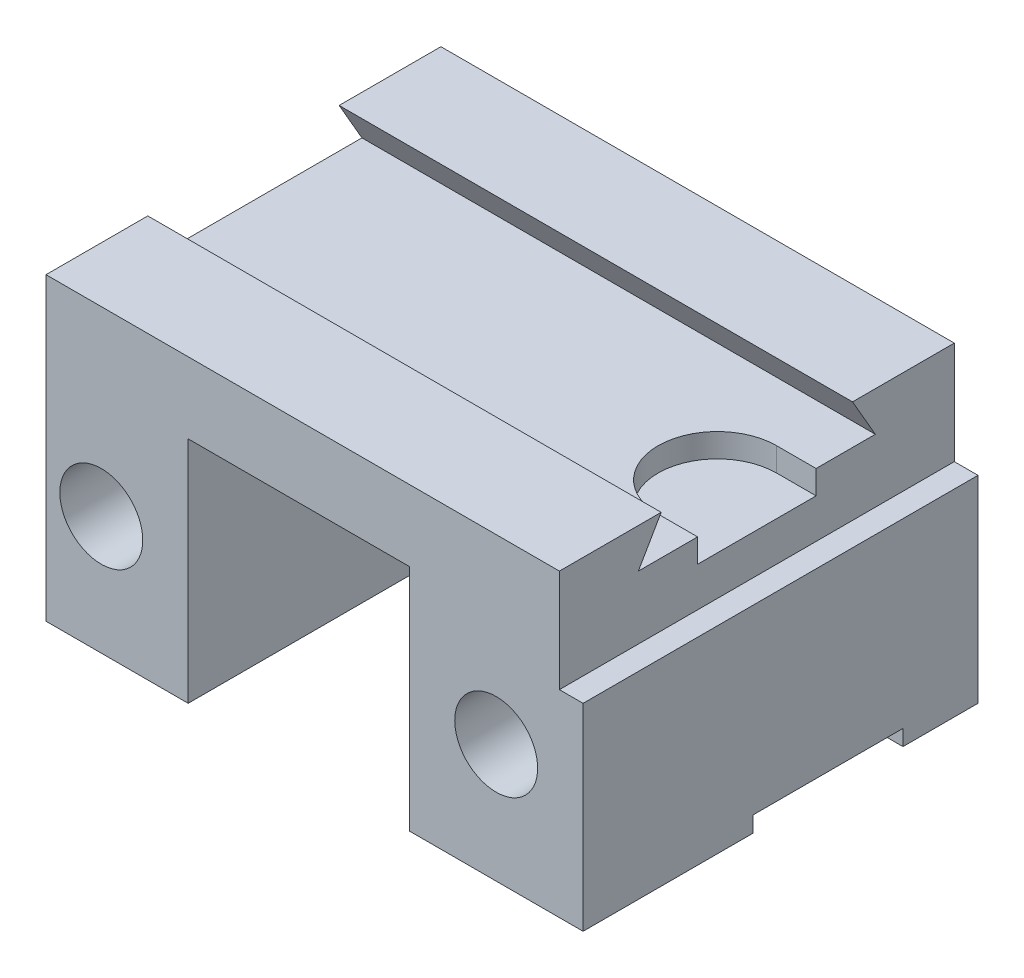
SolidWorks part; units mm, degrees
material "Polyetheretherketone (PEEK)"
ref_plane "Front Plane" through (0, 0, 0) normal (0, 0, 1) x (1, 0, 0)
ref_plane "Top Plane" through (0, 0, 0) normal (0, 1, 0) x (1, 0, 0)
ref_plane "Right Plane" through (0, 0, 0) normal (1, 0, 0) x (0, 0, -1)
ref_plane "Plane1" through (0, 4, 0) normal (0, 1, 0) x (-1, 0, 0)
sketch "Sketch1" plane through (0, 4, 0) normal (0, 1, 0) x (-1, 0, 0)
  line L0 (0, 0) -> (0, 5)
  line L1 (0, 5) -> (-6.8, 5)
  line L2 (-6.8, 5) -> (-6.8, 0)
  line L3 (-6.8, 0) -> (0, 0)
  dimension "D1" = 5
  dimension "D2" = 6.8
extrude "Boss-Extrude1" add sketch "Sketch1" against normal blind 3.8
sketch "Sketch3" plane through (0, 0, 5) normal (0, 0, 1) x (1, 0, 0)
  line L0 (1.8, 0.2) -> (4.6, 0.2)
  line L1 (4.6, 0.2) -> (4.6, 3.1)
  line L2 (4.6, 3.1) -> (1.8, 3.1)
  line L3 (1.8, 3.1) -> (1.8, 0.2)
  line L4 (0, 0.2) -> (6.8, 0.2) construction
  dimension "D1" = 2.8
  dimension "D2" = 2.9
extrude "Cut-Extrude2" cut sketch "Sketch3" against normal through all
sketch "Sketch4" plane through (6.8, 0, 0) normal (1, 0, 0) x (0, 0, -1)
  line L0 (-2.85, 0.2) -> (-0.95, 0.2)
  line L1 (-0.95, 0.2) -> (-0.95, 0.4)
  line L2 (-0.95, 0.4) -> (-2.85, 0.4)
  line L3 (-2.85, 0.4) -> (-2.85, 0.2)
  line L4 (-5, 0.2) -> (0, 0.2) construction
  dimension "D1" = 0.2
extrude "Cut-Extrude3" cut sketch "Sketch4" against normal blind 2.2
hole_wizard "Hole1" positions "Sketch7" profile "Sketch6" legacy end condition through all
sketch "Sketch7" plane through (0, 0, 0) normal (0, 0, -1) x (-1, 0, 0)
  point P0 (-5.7, 1.7)
  point P1 (-0.7, 1.7)
  dimension "D1" = 5
  dimension "D2" = 1.5
  dimension "D3" = 0.7
  dimension "D4" = 5.7
sketch "Sketch6" plane through (5.7, 1.7, 0) normal (1, 0, 0) x (0, 1, 0)
  line L0 (0, 0) -> (0, 5)
  line L1 (0, 5) -> (0.525, 5)
  line L2 (0.525, 5) -> (0.525, 1.2)
  line L3 (0.525, 1.2) -> (0.65, 1.2)
  line L4 (0.65, 1.2) -> (0.65, 0)
  line L5 (0.65, 0) -> (0, 0)
  line L6 (0, 110) -> (0, -10) construction
  dimension "Diameter" = 1.05
  dimension "Depth" = 5
  dimension "C-Bore Diameter" = 1.3
  dimension "C-Bore Depth" = 1.2
sketch "Sketch18" plane through (6.8, 0, 0) normal (1, 0, 0) x (0, 0, -1)
  line L0 (-3.7113, 4) -> (-4, 3.5)
  line L1 (-5, 4) -> (-5, 0.2) construction
  line L2 (-5, 4) -> (0, 4) construction
  line L3 (-4, 3.5) -> (-1, 3.5)
  line L4 (-1, 3.5) -> (-1.2887, 4)
  line L8 (-1.2887, 4) -> (-3.7113, 4)
  line M8 (0, 4) -> (-5, 4)
  dimension "D1" = 3
  dimension "D2" = 60
  dimension "D3" = 60
  dimension "D4" = 1
  dimension "D5" = 0.5
extrude "Cut-Extrude9" cut sketch "Sketch18" against normal through all contours L3 L4 L0 M8
sketch "Sketch19" plane through (0, 3.5, 0) normal (0, 1, 0) x (1, 0, 0)
  line L0 (6.8, -4) -> (6.8, -1) construction
  line L1 (6, -1.75) -> (6.8, -1.75)
  line L2 (6, -1.75) -> (6, -3.25)
  line L3 (6, -3.25) -> (6.8, -3.25)
  line L4 (6.8, -1.75) -> (6.8, -3.25)
  line L5 (6.8, 0) -> (0, 0) construction
  circle A0 centre (6, -2.5) radius 0.75
  line M1 (6.8, -4) -> (6.8, -1)
  dimension "D1" = 1.5
  dimension "D2" = 2.5
  dimension "D3" = 6
extrude "Cut-Extrude10" cut sketch "Sketch19" against normal blind 0.3 contours L2 A0 L3 | L3 A0 L2 | A0 L3 L1 M1
sketch "Sketch20" plane through (6.8, 0, 0) normal (1, 0, 0) x (0, 0, -1)
  line L0 (0, 0.2) -> (0, 4) construction
  line L1 (-5, 4) -> (0, 4)
  line L2 (-5, 4) -> (-5, 2.7)
  line L3 (-5, 2.7) -> (0, 2.7)
  line L4 (0, 4) -> (0, 2.7)
  dimension "D1" = 1.3
extrude "Cut-Extrude11" cut sketch "Sketch20" against normal blind 0.3
